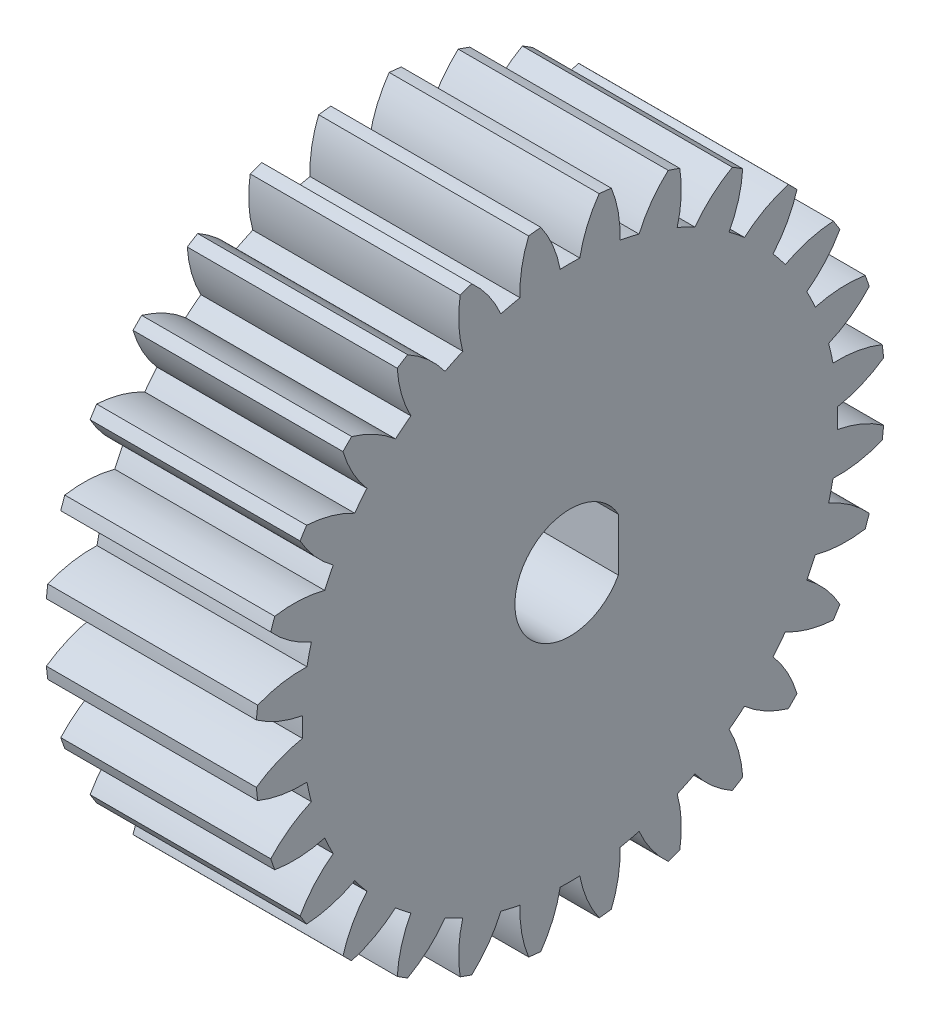
SolidWorks part; units mm, degrees
ref_plane "Plane1" through (0, 0, 0) normal (0, 0, 1) x (1, 0, 0)
ref_plane "Plane2" through (0, 0, 0) normal (0, 1, 0) x (1, 0, 0)
ref_plane "Plane3" through (0, 0, 0) normal (1, 0, 0) x (0, 0, -1)
other "Configuration Table"
sketch "HoldingSke" plane through (0, 0, 0) normal (0, 1, 0) x (1, 0, 0)
  line L0 (0, 0) -> (0.7064, -0.3756)
  line L1 (-15, 0) -> (100, 0) construction
  line L2 (0, 0) -> (-2.1039, 2.3779)
  line L3 (0, 0) -> (-11.863, 4.5341)
  line L4 (0, 0) -> (7.6251, 4.0544)
  line L5 (0, 0) -> (-46.8476, -17.4728)
  line L6 (0, 0) -> (-10.362, -6.9913)
  line L7 (-2.1039, 2.3779) -> (8.6586, 51.2059)
  line L8 (-76.2, 54.61) -> (-75.9, 54.61)
  line L9 (-71.009, 38.7566) -> (-53.1078, 45.2721)
  line L10 (-76.2, 71.12) -> (104.1128, 71.12)
  line L11 (0, 0) -> (-12.5, 0)
  line L12 (-76.2, 101.6) -> (-76.155, 101.6)
  line L13 (24.9733, 27.94) -> (52.9518, 28.4284)
  line L14 (24.9733, 27.94) -> (24.9743, 27.94)
  line L15 (24.9733, 27.94) -> (100.4006, 29.5858)
  line L16 (-63.627, -1.25) -> (-12.827, -1.25)
  circle A0 centre (0, 0) radius 1
  circle A1 centre (0, 0) radius 15.9365
  circle A2 centre (0, 0) radius 37.5
  circle A3 centre (0, 0) radius 1
  dimension "MHD" = 31.873
  dimension "Hub_dia" = 75
  dimension "Bore" = 2
  dimension "MBD" = 2
  dimension "Num_teeth" = 28
  dimension "Pitch" = 0.8
  dimension "Overall_len" = 50
  dimension "Show_teeth" = 28
  dimension "Thickness" = 12.5
  dimension "OAL" = 50.0001
  dimension "T_dim" = 0.3
  dimension "Ap" = 20
  dimension "H" = 19.05
  dimension "Pitch_radius" = 180.3128
  dimension "Width" = 12.5
  dimension "Backlash" = 0.045
  dimension "Addendum_fac" = 1
  dimension "Dedendum_fac" = 1.25
  dimension "Clearance_fac" = 0.25
  dimension "Dedendum_add" = 0.001
  dimension "Module" = 1.25
sketch "BasProSke" plane through (0, 0, 0) normal (0, 1, 0) x (1, 0, 0)
  line L0 (-10, 0) -> (60, 0) construction
  line L1 (0, 0) -> (0, 18.75)
  line L2 (0, 0) -> (12.5, 0)
  line L3 (12.5, 0) -> (12.5, 18.75)
  line L4 (12.5, 18.75) -> (0, 18.75)
  dimension "Thickness" = 12.5
  dimension "Diameter" = 37.5
revolve "Base-Revolve" add sketch "BasProSke" angle 360 about L0
sketch "TooCutSke" plane through (0, 0, 0) normal (1, 0, 0) x (0, 0, -1)
  line L1 (0, 0) -> (0, 107) construction
  line L2 (0, 0) -> (-1.06, 17.4679) construction
  line L3 (0, 0) -> (-3.9135, 34.7336) construction
  line L4 (-1.06, 17.4679) -> (-1.9568, 17.3668) construction
  arc A0 (0.5852, 15.9258) -> (-0.5852, 15.9258) centre (0, 0) ccw
  arc A1 (1.7533, 18.6934) -> (-1.7533, 18.6934) centre (0, 0) ccw
  circle A2 centre (0, 0) radius 17.5 construction
  circle A3 centre (0, 0) radius 16.4446 construction
  arc A4 (-0.5852, 15.9258) -> (-1.7533, 18.6934) centre (-7.4682, 14.651) ccw
  arc A5 (1.7533, 18.6934) -> (0.5852, 15.9258) centre (7.4682, 14.651) ccw
  dimension "Root_dia" = 31.873
  dimension "Overcut_dia" = 37.5508
  dimension "Pitch_dia" = 35
  dimension "Base_dia" = 32.8892
  dimension "Flank_rad" = 7
  dimension "Half_ang" = 6.429
  dimension "Half_CT" = 0.9025
extrude "ToothCut" cut sketch "TooCutSke" along normal through all
fillet "Breaks" [suppressed] radius 0.025
fillet "RootFillets" [suppressed] radius 0.3135
pattern_circular "TeethCuts" count 28 every 12.857 about axis through (-10, 0, 0) along (1, 0, 0) of "ToothCut", "RootFillets", "Breaks"
sketch "HubNeaOneSke" plane through (0, 0, 0) normal (-1, 0, 0) x (0, 0, 1)
  circle A0 centre (0, 0) radius 15.9365
  dimension "Diameter" = 31.873
extrude "HubNearOne" [suppressed] add sketch "HubNeaOneSke" along normal blind 37.5001
sketch "HubNeaBotSke" plane through (0, 0, 0) normal (-1, 0, 0) x (0, 0, 1)
  circle A0 centre (0, 0) radius 15.9365
  dimension "Diameter" = 31.873
extrude "HubNearBoth" [suppressed] add sketch "HubNeaBotSke" along normal blind 18.75
ref_plane "FarPln" through (12.5, 0, 0) normal (1, 0, 0) x (0, 0, -1)
sketch "HubFarSke" plane through (12.5, 0, 0) normal (1, 0, 0) x (0, 0, -1)
  circle A0 centre (0, 0) radius 15.9365
  dimension "Diameter" = 31.873
extrude "HubFar" [suppressed] add sketch "HubFarSke" along normal blind 18.75
sketch "BorSke" plane through (0, 0, 0) normal (1, 0, 0) x (0, 0, -1)
  circle A0 centre (0, 0) radius 1
  dimension "Diameter" = 2
extrude "Bore" cut sketch "BorSke" along normal mid plane 100.0001
sketch "KeySke" plane through (0, 0, 0) normal (1, 0, 0) x (0, 0, -1)
  line L0 (-0.4, 0) -> (-0.4, 1.3)
  line L1 (-0.4, 1.3) -> (0.4, 1.3)
  line L2 (0.4, 1.3) -> (0.4, 0)
  line L3 (0, 0) -> (0, 34) construction
  line L4 (-0.4, 0) -> (0.4, 0)
  dimension "Offset" = 1.3
  dimension "Width" = 0.8
extrude "Keyway" [suppressed] cut sketch "KeySke" along normal mid plane 100.0001
pattern_circular "Keyway2" [suppressed] count 2 every 90 about axis through (-10, 0, 0) along (1, 0, 0)
sketch "Sketch1" plane through (0, 0, 0) normal (-1, 0, 0) x (0, 0, 1)
  line L0 (-2.88, 1.5697) -> (-2.88, -1.5697)
  arc A0 (-2.88, -1.5697) -> (-2.88, 1.5697) centre (0, 0) ccw
  dimension "D1" = 6.56
  dimension "D2" = 2.88
extrude "Cut-Extrude1" cut sketch "Sketch1" against normal through all
sketch "Sketch2" plane through (0, 0, 0) normal (-1, 0, 0) x (0, 0, 1)
  circle A0 centre (0, 0) radius 3.28
extrude "Boss-Extrude1" add sketch "Sketch2" against normal blind 1.5 contours A0
equation "' \"Module@HoldingSke\" = 6.35"
equation "' \"Num_teeth@HoldingSke\" = 12"
equation "' \"Ap@HoldingSke\" =  20"
equation "' \"Ap@HoldingSke\" = 20"
equation "' \"Width@HoldingSke\" = 0.5 * 25.4"
equation "' \"Hub_dia@HoldingSke\"= 1 * 25.4"
equation "' \"Hub_dia@HoldingSke\" = 1 * 25.4"
equation "' \"Overall_len@HoldingSke\" = 1.0 * 25.4"
equation "' \"Bore@HoldingSke\" = 0.75 * 25.4"
equation "' \"T_dim@HoldingSke\" = 0.1 * 25.4"
equation "' \"Width@KeySke\" = 0.25 * 25.4"
equation "' \"Show_teeth@HoldingSke\" = 13"
equation "' \"Backlash@HoldingSke\" = 0.009 * 25.4"
equation "' \"Addendum_fac@HoldingSke\" = 1.0"
equation "' \"Dedendum_fac@HoldingSke\" = 1.25"
equation "' \"Dedendum_add@HoldingSke\" = 0.00005 * 25.4"
equation "' \"Clearance_fac@HoldingSke\" = 0.25"
equation "\"Pitch@HoldingSke\" = 1 / \"Module@HoldingSke\""
equation "\"Overcut_dia@TooCutSke\" = (\"Num_teeth@HoldingSke\" + 2 * \"Addendum_fac@HoldingSke\") / \"Pitch@HoldingSke\" + 0.002 * 25.4"
equation "\"Pitch_dia@TooCutSke\" = \"Num_teeth@HoldingSke\" / \"Pitch@HoldingSke\""
equation "\"Base_dia@TooCutSke\" = \"Num_teeth@HoldingSke\" / \"Pitch@HoldingSke\" * cos((\"Ap@HoldingSke\"  * 3.14159265 / 180))"
equation "\"Root_dia@TooCutSke\" = (\"Num_teeth@HoldingSke\" + 2) / \"Pitch@HoldingSke\" - 2 * (\"Addendum_fac@HoldingSke\" + \"Dedendum_fac@HoldingSke\") / \"Pitch@HoldingSke\" - \"Dedendum_add@HoldingSke\" * 2"
equation "\"Half_ang@TooCutSke\" = 180 / \"Num_teeth@HoldingSke\""
equation "\"Half_CT@TooCutSke\" = \"Num_teeth@HoldingSke\" / \"Pitch@HoldingSke\" * sin((3.14159265 / 2 / \"Num_teeth@HoldingSke\")) / 2 - 7 * \"Backlash@HoldingSke\" / 4"
equation "\"Flank_rad@TooCutSke\" = \"Num_teeth@HoldingSke\" / \"Pitch@HoldingSke\" / 5"
equation "\"Radius@RootFillets\" = \"Clearance_fac@HoldingSke\" / \"Pitch@HoldingSke\" + \"Dedendum_add@HoldingSke\""
equation "\"Break_rad@Breaks\" = 0.02 / \"Pitch@HoldingSke\""
equation "\"Thickness@HoldingSke\" = \"Width@HoldingSke\""
equation "\"OAL@HoldingSke\" = \"Thickness@HoldingSke\""
equation "\"MHD@HoldingSke\" = (\"Num_teeth@HoldingSke\" + 2) / \"Pitch@HoldingSke\" - 2 * (\"Addendum_fac@HoldingSke\" + \"Dedendum_fac@HoldingSke\")  / \"Pitch@HoldingSke\" - \"Dedendum_add@HoldingSke\" * 2"
equation "\"MBD@HoldingSke\" = (\"Num_teeth@HoldingSke\" + 2) / \"Pitch@HoldingSke\" - 2 * (\"Addendum_fac@HoldingSke\" + \"Dedendum_fac@HoldingSke\")  / \"Pitch@HoldingSke\" - \"Dedendum_add@HoldingSke\" * 2 - 0.002 * 25.4"
equation "\"MHD@HoldingSke\" = ((sgn( \"MHD@HoldingSke\" - \"Hub_dia@HoldingSke\" )-1)*( \"MHD@HoldingSke\" - \"Hub_dia@HoldingSke\" ))/-2+ \"Hub_dia@HoldingSke\""
equation "\"MBD@HoldingSke\" = ((sgn( \"MBD@HoldingSke\" - \"Bore@HoldingSke\" )-1)*( \"MBD@HoldingSke\" - \"Bore@HoldingSke\" ))/-2+ \"Bore@HoldingSke\""
equation "\"OAL@HoldingSke\" = ((sgn( \"OAL@HoldingSke\" - \"Overall_len@HoldingSke\" )+1)*( \"OAL@HoldingSke\" - \"Overall_len@HoldingSke\" ))/2 + \"Overall_len@HoldingSke\" + 0.000002 * 25.4"
equation "\"Num_teeth@TeethCuts\" = int( \"Show_teeth@HoldingSke\" ) + 1"
equation "\"Num_teeth@TeethCuts\" = ((sgn( \"Num_teeth@TeethCuts\" - \"Num_teeth@HoldingSke\" )-1)*( \"Num_teeth@TeethCuts\" - \"Num_teeth@HoldingSke\" ))/-2+ \"Num_teeth@HoldingSke\""
equation "\"Num_teeth@TeethCuts\" = ((sgn( \"Num_teeth@TeethCuts\" - 2.0)+1)*( \"Num_teeth@TeethCuts\" - 2.0))/2 +2.0"
equation "\"Angle@TeethCuts\" = 360.0 / \"Num_teeth@HoldingSke\""
equation "\"Diameter@BasProSke\" = (\"Num_teeth@HoldingSke\" + 2 * \"Addendum_fac@HoldingSke\") / \"Pitch@HoldingSke\""
equation "\"Thickness@BasProSke\"  = \"Thickness@HoldingSke\""
equation "' \"Fillet_rad@BasProSke\" =  \"Thickness@HoldingSke\" * 0.05"
equation "' \"Fillet_rad@BasProSke\" = \"Thickness@HoldingSke\" * 0.05"
equation "\"MHD@HoldingSke\" = ((sgn( \"MHD@HoldingSke\" - \"Root_dia@TooCutSke\" )-1)*( \"MHD@HoldingSke\" - \"Root_dia@TooCutSke\" ))/-2+ \"Root_dia@TooCutSke\""
equation "\"Diameter@HubNeaOneSke\" = \"MHD@HoldingSke\""
equation "\"Length@HubNearOne\" = \"OAL@HoldingSke\" - \"Thickness@BasProSke\""
equation "\"Diameter@HubNeaBotSke\" = \"MHD@HoldingSke\""
equation "\"Length@HubNearBoth\" = ( \"OAL@HoldingSke\" - \"Thickness@BasProSke\" ) / 2.0"
equation "\"Thickness@FarPln\" = \"Thickness@BasProSke\""
equation "\"Diameter@HubFarSke\" = \"MHD@HoldingSke\""
equation "\"Length@HubFar\" = ( \"OAL@HoldingSke\" - \"Thickness@BasProSke\" ) / 2.0"
equation "\"Diameter@BorSke\" = \"MBD@HoldingSke\""
equation "\"D1@Bore\" = \"OAL@HoldingSke\" * 2.0"
equation "\"D1@Keyway\" = \"OAL@HoldingSke\" * 2.0"
equation "\"Offset@KeySke\" = \"T_dim@HoldingSke\" + \"MBD@HoldingSke\" / 2.0"
